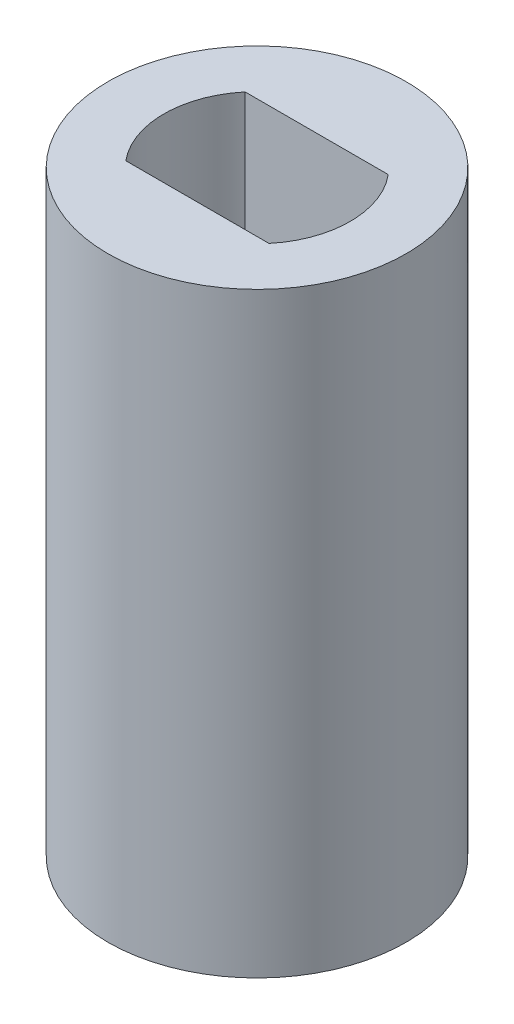
SolidWorks part; units mm, degrees
ref_plane "Front Plane" through (0, 0, 0) normal (0, 0, 1) x (1, 0, 0)
ref_plane "Top Plane" through (0, 0, 0) normal (0, 1, 0) x (1, 0, 0)
ref_plane "Right Plane" through (0, 0, 0) normal (1, 0, 0) x (0, 0, -1)
sketch "Sketch1" plane through (0, 0, 0) normal (0, 1, 0) x (1, 0, 0)
  circle A0 centre (0, 0) radius 2.5
  circle A1 centre (0, 0) radius 4
  dimension "D1" = 5
  dimension "D2" = 8
extrude "Boss-Extrude1" add sketch "Sketch1" along normal blind 11
sketch "Sketch2" plane through (0, 11, 0) normal (0, 1, 0) x (1, 0, 0)
  line L0 (0, 0) -> (0, 1.6) construction
  line L1 (1.9209, 1.6) -> (-1.9209, 1.6)
  line L2 (0, 0) -> (-2.5, 0) construction
  line L3 (1.9209, -1.6) -> (-1.9209, -1.6)
  circle A0 centre (0, 0) radius 4
  arc A1 (-1.9209, 1.6) -> (-1.9209, -1.6) centre (0, 0) ccw
  circle A2 centre (0, 0) radius 2.5 construction
  arc A3 (1.9209, -1.6) -> (1.9209, 1.6) centre (0, 0) ccw
  point P7 (0, 1.6)
  dimension "D1" = 1.6
extrude "Boss-Extrude2" add sketch "Sketch2" along normal blind 5
